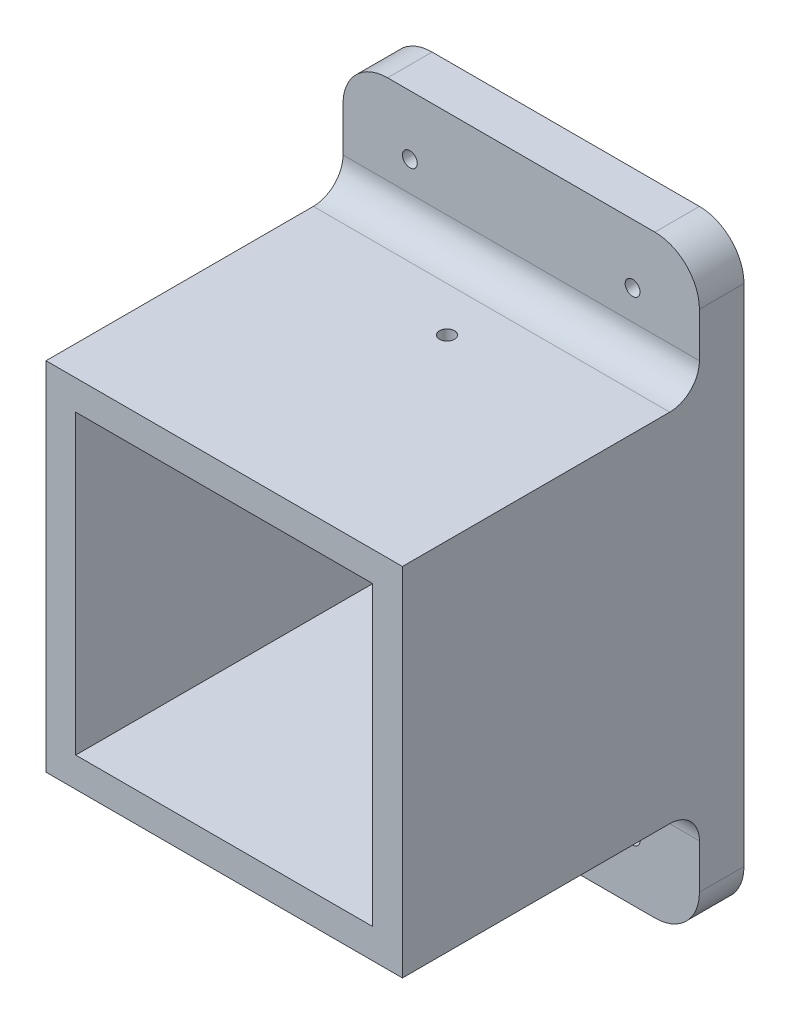
SolidWorks part; units mm, degrees
material "Rubber"
ref_plane "Front Plane" through (0, 0, 0) normal (1, 0, 0) x (0, 1, 0)
ref_plane "Top Plane" through (0, 0, 0) normal (0, 0, 1) x (0, 1, 0)
ref_plane "Right Plane" through (0, 0, 0) normal (0, 1, 0) x (-1, 0, 0)
sketch "Sketch1" plane through (0, 0, 0) normal (0, 0, 1) x (0, 1, 0)
  line L0 (-50, 50) -> (50, 50)
  line L1 (-60, 60) -> (60, 60)
  line L2 (-60, 60) -> (-60, -60)
  line L3 (-60, -60) -> (60, -60)
  line L4 (60, 60) -> (60, -60)
  line L5 (50, 50) -> (50, -50)
  line L6 (-50, -50) -> (50, -50)
  line L7 (-50, 50) -> (-50, -50)
  point P5 (-60, 0)
  point P6 (0, 60)
  dimension "D1" = 120
  dimension "D2" = 120
  dimension "D3" = 0
  dimension "D4" = 0
  dimension "D5" = 10
extrude "Boss-Extrude1" add sketch "Sketch1" along normal blind 100
sketch "Sketch2" plane through (0, 0, 0) normal (0, 0, -1) x (1, 0, 0)
  line L1 (60, 100) -> (-60, 100)
  line L2 (60, 100) -> (60, -100)
  line L3 (60, -100) -> (-60, -100)
  line L4 (60, 60) -> (-60, 60)
  line L5 (-60, 60) -> (-60, -60)
  line L6 (-60, -60) -> (60, -60)
  line L7 (60, -60) -> (60, 60)
  line L8 (60, 60) -> (-60, 60)
  line L9 (-60, 60) -> (-60, -60)
  line L10 (-60, -60) -> (60, -60)
  line L11 (60, -60) -> (60, 60)
  line L12 (-60, 100) -> (-60, -100)
  point P8 (60, 0)
  line M9 (60, 60) -> (-60, 60)
  line M10 (-60, 60) -> (-60, -60)
  line M11 (-60, -60) -> (60, -60)
  line M12 (60, -60) -> (60, 60)
  line M13 (-50, 50) -> (50, 50)
  line M14 (50, 50) -> (50, -50)
  line M15 (50, -50) -> (-50, -50)
  line M16 (-50, -50) -> (-50, 50)
  dimension "D2" = 0
  dimension "D3" = 0
  dimension "D4" = 0
  dimension "D5" = 200
  dimension "D1" = 0
extrude "Boss-Extrude2" add sketch "Sketch2" along normal blind 15 contours L1 L12 L2 M9 | L12 L3 L2 M11 | M12 M9 M10 M11 M16 M13 M14 M15 | M13 M16 M15 M14
sketch "Sketch3" plane through (0, 0, -15) normal (0, 0, -1) x (1, 0, 0)
  line L1 (-37.5, 80) -> (37.5, 80)
  line L2 (-37.5, 80) -> (-37.5, -80)
  line L3 (-37.5, -80) -> (37.5, -80)
  line L4 (60, 100) -> (-60, 100)
  line L5 (-60, 100) -> (-60, -100)
  line L6 (-60, -100) -> (60, -100)
  line L7 (60, -100) -> (60, 100)
  line L8 (60, 100) -> (-60, 100)
  line L9 (-60, 100) -> (-60, -100)
  line L10 (-60, -100) -> (60, -100)
  line L11 (60, -100) -> (60, 100)
  line L12 (37.5, 80) -> (37.5, -80)
  point P8 (0, 80)
  point P9 (0, 100)
  point P10 (-37.5, 0)
  point P11 (-60, 0)
  point P13 (-37.5, 80)
  point P14 (37.5, 80)
  point P15 (-37.5, -80)
  point P16 (37.5, -80)
  point P17 (0, 0)
  dimension "D2" = 0
  dimension "D3" = 0
  dimension "D4" = 75
  dimension "D5" = 160
  dimension "D1" = 0
hole_wizard "Ø5.0mm Dowel Hole2" positions "Sketch3" profile "Sketch4" hole size "Ø5.0" standard "IS" end condition through all
sketch "Sketch4" plane through (37.5, 80, -15) normal (1, 0, 0) x (0, 1, 0)
  line L0 (0, 0) -> (0, 115)
  line L1 (0, 115) -> (2.5, 115)
  line L2 (2.5, 115) -> (2.5, 0.025)
  line L3 (2.5, 0.025) -> (2.525, 0)
  line L5 (2.525, 0) -> (0, 0)
  line L6 (-2.5, 0.025) -> (-2.525, 0) construction
  line L11 (0, -6.35) -> (0, 107.95) construction
  dimension "Thru Hole Dia." = 5
  dimension "Thru Hole Depth" = 115
  dimension "Near C'Sink Dia." = 5.05
  dimension "Near C'Sink Angle" = 90
sketch "Sketch5" plane through (0, 60, 0) normal (0, 1, 0) x (-1, 0, 0)
  point P0 (0, 25)
  dimension "D1" = 0
  dimension "D2" = 25
hole_wizard "Ø5.0mm Dowel Hole1" positions "Sketch5" profile "Sketch6" hole size "Ø5.0" standard "IS" end condition through all
sketch "Sketch6" plane through (0, 60, 25) normal (1, 0, 0) x (0, 0, 1)
  line L0 (0, 0) -> (0, 160)
  line L1 (0, 160) -> (2.5, 160)
  line L2 (2.5, 160) -> (2.5, 0.025)
  line L3 (2.5, 0.025) -> (2.525, 0)
  line L5 (2.525, 0) -> (0, 0)
  line L6 (-2.5, 0.025) -> (-2.525, 0) construction
  line L11 (0, -6.35) -> (0, 107.95) construction
  dimension "Thru Hole Dia." = 5
  dimension "Thru Hole Depth" = 160
  dimension "Near C'Sink Dia." = 5.05
  dimension "Near C'Sink Angle" = 90
fillet "Fillet1" radius 15 4 edges at (-60, -100, -7.5) (60, -100, -7.5) (-60, 100, -7.5) (60, 100, -7.5)
fillet "Fillet2" radius 10 2 edges at (0, 60, 0) (0, -60, 0)
